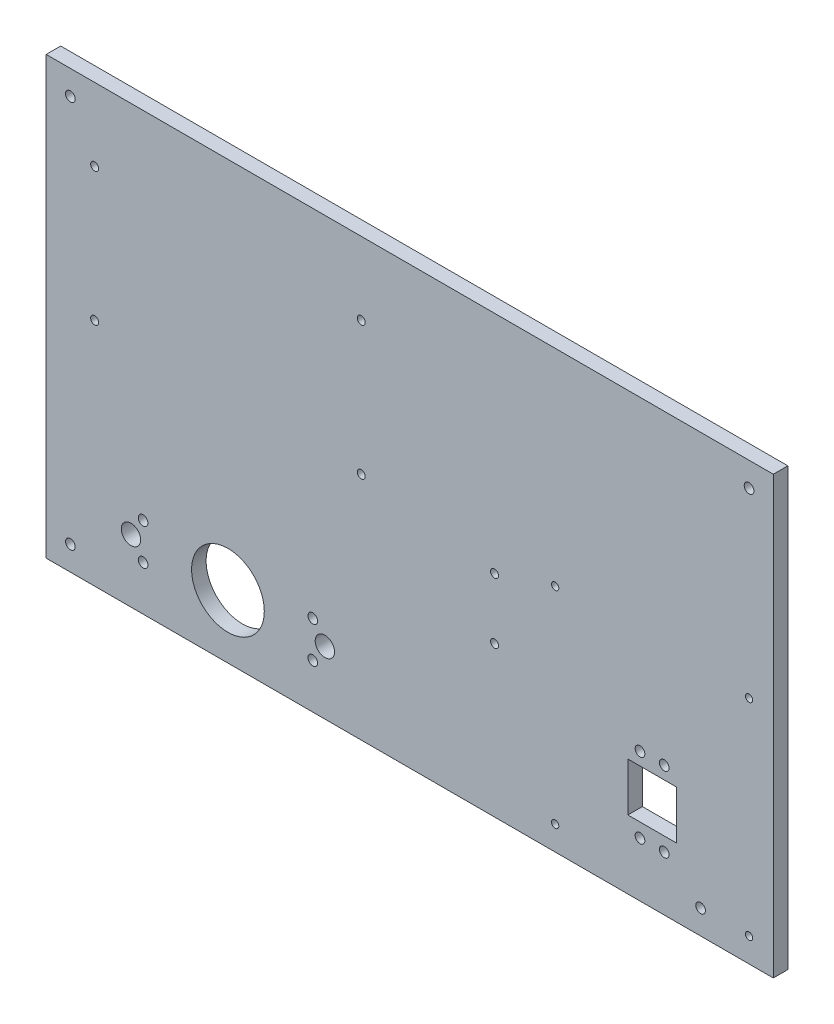
SolidWorks part; units mm, degrees
material "Faia"
ref_plane "Plano frontal" through (0, 0, 0) normal (0, 0, 1) x (1, 0, 0)
ref_plane "Plano superior" through (0, 0, 0) normal (0, 1, 0) x (1, 0, 0)
ref_plane "Plano direito" through (0, 0, 0) normal (1, 0, 0) x (0, 0, -1)
sketch "Esboço1" plane through (0, 0, 0) normal (0, 0, 1) x (1, 0, 0)
  line L0 (150, 0) -> (-150, 0) construction
  line L1 (-150, 90) -> (150, 90)
  line L2 (-150, 90) -> (-150, -90)
  line L3 (-150, -90) -> (150, -90)
  line L4 (150, 90) -> (150, -90)
  line L5 (-150, 90) -> (150, -90) construction
  line L6 (-150, -90) -> (150, 90) construction
  line L7 (70, 0) -> (-230, 0) construction
  line L8 (-83.2276, -64) -> (-64.3617, -64) construction
  line L9 (60, 5) -> (60, -80) construction
  line L10 (140, 5) -> (60, 5) construction
  line L11 (60, -80) -> (140, -80) construction
  line L12 (-75, -58.1086) -> (-75, -85.356) construction
  line L13 (90, -41.75) -> (110, -41.75)
  line L14 (90, -41.75) -> (90, -61.75)
  line L15 (90, -61.75) -> (110, -61.75)
  line L16 (110, -41.75) -> (110, -61.75)
  line L17 (90, -41.75) -> (110, -61.75) construction
  line L18 (90, -61.75) -> (110, -41.75) construction
  line L20 (-20, 5) -> (-130, 5) construction
  line L21 (-20, 5) -> (-20, 60) construction
  line L22 (-20, 60) -> (-130, 60) construction
  line L23 (-130, 5) -> (-130, 60) construction
  line L24 (-20, 5) -> (-130, 60) construction
  line L25 (-20, 60) -> (-130, 5) construction
  circle A0 centre (140, 5) radius 1.5
  circle A1 centre (140, -80) radius 1.5
  circle A2 centre (60, -80) radius 1.5
  circle A3 centre (60, 5) radius 1.5
  circle A4 centre (-110, -56.5) radius 2
  circle A5 centre (-40, -56.5) radius 2
  circle A6 centre (-75, -64) radius 15
  circle A7 centre (-35, -64) radius 4
  circle A8 centre (-115, -64) radius 4
  circle A9 centre (-40, -71.5) radius 2
  circle A10 centre (-110, -71.5) radius 2
  circle A11 centre (35, -3) radius 1.65
  circle A12 centre (35, -28) radius 1.65
  circle A13 centre (-130, 60) radius 1.65
  circle A14 centre (-20, 60) radius 1.65
  circle A15 centre (-20, 5) radius 1.65
  circle A16 centre (-130, 5) radius 1.65
  point P0 (0, 0)
  point P21 (5, 0)
  point P23 (100, -51.75)
  point P28 (100, -80)
  point P48 (-75, 32.5)
  point P56 (-75, 54.542)
  dimension "D5" = 3
  dimension "D8" = 35
  dimension "D16" = 30
  dimension "D19" = 8
  dimension "D20" = 80
  dimension "D10" = 4
  dimension "D21" = 3.3
  dimension "D26" = 3.3
  dimension "D1" = 300
  dimension "D2" = 180
  dimension "D3" = 10
  dimension "D4" = 85
  dimension "D7" = 80
  dimension "D9" = 15
  dimension "D11" = 25
  dimension "D12" = 10
  dimension "D13" = 20
  dimension "D14" = 20
  dimension "D15" = 28.25
  dimension "D17" = 75
  dimension "D18" = 26
  dimension "D22" = 25
  dimension "D23" = 8
  dimension "D24" = 55
  dimension "D25" = 110
  dimension "D27" = 30
  dimension "D28" = 20
  dimension "D6" = 2
extrude "Ressalto-extrusão1" add sketch "Esboço1" along normal blind 6 contours L4 L1 L2 L3 A3 A1 A0 A2
sketch "Esboço2" plane through (0, 0, 6) normal (0, 0, 1) x (1, 0, 0)
  line L0 (150, 0) -> (-150, 0) construction
  line L1 (-150, 90) -> (150, 90)
  line L2 (-150, 90) -> (-150, -90)
  line L3 (-150, -90) -> (150, -90)
  line L4 (150, 90) -> (150, -90)
  line L5 (-150, 90) -> (150, -90) construction
  line L6 (-150, -90) -> (150, 90) construction
  line L7 (140, 80) -> (140, 90) construction
  line L8 (120, -80) -> (120, -90) construction
  circle A0 centre (120, -80) radius 2
  circle A1 centre (140, 80) radius 2
  circle A2 centre (-140, 80) radius 2
  circle A3 centre (-140, -80) radius 2
  point P0 (0, 0)
  point P16 (0.5357, 0)
  dimension "D3" = 4
  dimension "D1" = 300
  dimension "D2" = 180
  dimension "D4" = 10
  dimension "D5" = 30
  dimension "D6" = 10
  dimension "D7" = 10
extrude "Corte-extrusão1" cut sketch "Esboço2" against normal blind 10 contours A2 | A1 | A0 | A3
sketch "Esboço3" plane through (0, 0, 6) normal (0, 0, 1) x (1, 0, 0)
  line L0 (150, 90) -> (150, -90) construction
  line L1 (-150, -90) -> (150, -90) construction
  circle A0 centre (105, -67.5) radius 2
  circle A1 centre (105, -36.5) radius 2
  circle A2 centre (95, -36.5) radius 2
  circle A3 centre (95, -67.5) radius 2
  point P12 (0, 0)
  point P13 (0, 0)
  point P14 (0, 0)
  point P15 (0, 0)
  dimension "D2" = 4
  dimension "D1" = 45
  dimension "D3" = 22.5
  dimension "D4" = 31
  dimension "D5" = 10
extrude "Corte-extrusão2" cut sketch "Esboço3" against normal blind 10
